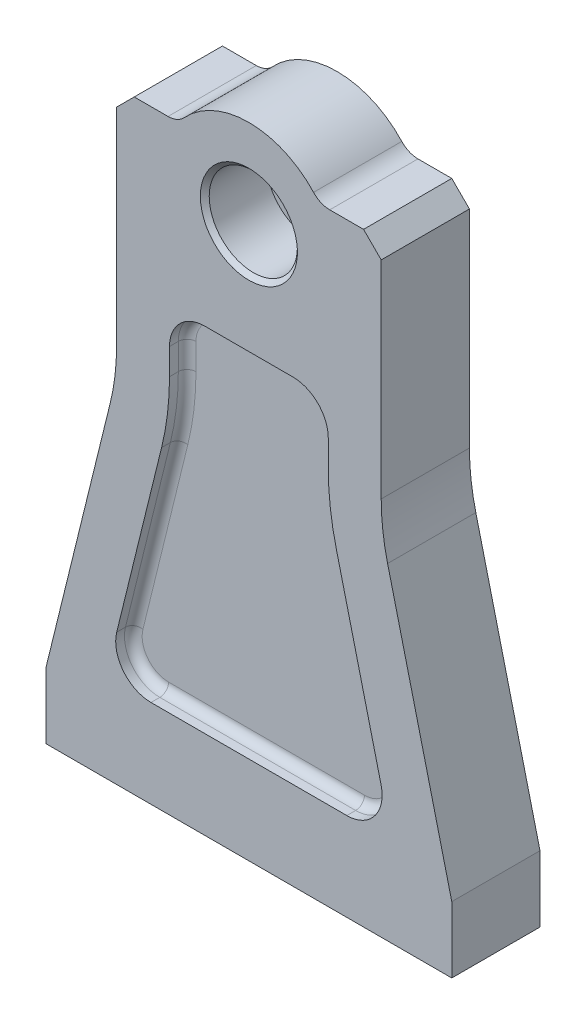
SolidWorks part; units mm, degrees
ref_plane "Front Plane" through (0, 0, 0) normal (0, 0, 1) x (1, 0, 0)
ref_plane "Top Plane" through (0, 0, 0) normal (0, 1, 0) x (1, 0, 0)
ref_plane "Right Plane" through (0, 0, 0) normal (1, 0, 0) x (0, 0, -1)
sketch "Sketch1" plane through (0, 0, 0) normal (0, 0, 1) x (1, 0, 0)
  line L0 (-46, 0) -> (46, 0)
  line L1 (46, 0) -> (46, 15)
  line L2 (46, 15) -> (31.4493, 74.1124)
  line L3 (30, 86.0633) -> (30, 137)
  line L4 (16, 137) -> (30, 137)
  line L5 (0, 0) -> (0, 200.804) construction
  line L6 (-16, 137) -> (-30, 137)
  line L7 (-30, 86.0633) -> (-30, 137)
  line L8 (-46, 15) -> (-31.4493, 74.1124)
  line L9 (-46, 0) -> (-46, 15)
  arc A0 (16, 137) -> (-16, 137) centre (0, 125) ccw
  circle A1 centre (0, 125) radius 6.5
  arc A2 (31.4493, 74.1124) -> (30, 86.0633) centre (80, 86.0633) cw
  arc A3 (-31.4493, 74.1124) -> (-30, 86.0633) centre (-80, 86.0633) ccw
  point P17 (30, 80)
  point P20 (-30, 80)
  dimension "D1" = 13
  dimension "D2" = 40
  dimension "D9" = 50
  dimension "D3" = 125
  dimension "D4" = 46
  dimension "D5" = 15
  dimension "D6" = 65
  dimension "D7" = 12
  dimension "D8" = 30
extrude "Boss-Extrude1" add sketch "Sketch1" along normal mid plane 20
sketch "Sketch2" plane through (0, 0, 10) normal (0, 0, 1) x (1, 0, 0)
  circle A0 centre (0, 125) radius 10
  dimension "D1" = 20
extrude "Cut-Extrude1" cut sketch "Sketch2" against normal blind 14
chamfer "Chamfer1" distance 1 angle 45 1 edges at (10, 125, 10)
chamfer "Chamfer2" distance 4 angle 45 2 edges at (30, 137, 0) (-30, 137, 0)
fillet "Fillet1" radius 5 2 edges at (16, 137, 0) (-16, 137, 0)
sketch3d "3DSketch3"
  line L0 (-18, 137.0109, 10) -> (-18, 86.0633, 10)
  line L1 (-19.7971, 71.2442, 10) -> (-37.3341, 0, 10)
  line L2 (-18, 137.0109, 10) -> (-18, 86.0633, 10)
  line L3 (-19.7971, 71.2442, 10) -> (-37.3341, 0, 10)
  line L4 (37.3341, 0, 10) -> (19.7971, 71.2442, 10)
  line L5 (18, 86.0633, 10) -> (18, 137.0109, 10)
  line L6 (37.3341, 0, 10) -> (19.7971, 71.2442, 10)
  line L7 (18, 86.0633, 10) -> (18, 137.0109, 10)
  spline S0 degree 5 poles (979.9272, 150.3528, 10) (366.7072, 141.5048, 10) (67.5037, 129.3382, 10) (-24.8839, 114.9859, 10) (-17.3153, 98.854, 10) (-18.0647, 82.8101, 10) (-18.1123, 82.0877, 10) (-18.2404, 80.5075, 10) (-18.4062, 78.9316, 10) (-18.5092, 78.0771, 10) (-18.7138, 76.5948, 10) (-18.9684, 75.1206, 10) (-19.0848, 74.4955, 10) (-19.2618, 73.6027, 10) (-19.4521, 72.7126, 10) (-19.511, 72.4447, 10) (-22.0166, 61.4386, 10) (-28.4768, 51.3904, 10) (62.2357, 18.0877, 10) (350.7446, -63.1243, 10) (937.8308, -216.6557, 10) knots -5.002278 -5.002278 -5.002278 -5.002278 -5.002278 -5.002278 0.120836 0.120836 0.120836 0.362509 0.362509 0.362509 0.650011 0.650011 0.650011 0.862509 0.862509 0.862509 0.95417 0.95417 0.95417 4.634695 4.634695 4.634695 4.634695 4.634695 4.634695 only from (-18, 86.0633, 10) to (-19.7971, 71.2442, 10)
  spline S1 degree 5 poles (-18, 86.0633, 10) (-18, 85.7018, 10) (-18, 85.3402, 10) (-18.0014, 84.9787, 10) (-18.0141, 83.8942, 10) (-18.0647, 82.8101, 10) (-18.1123, 82.0877, 10) (-18.2404, 80.5075, 10) (-18.4062, 78.9316, 10) (-18.5092, 78.0771, 10) (-18.7138, 76.5948, 10) (-18.9684, 75.1206, 10) (-19.0848, 74.4955, 10) (-19.2618, 73.6027, 10) (-19.4521, 72.7126, 10) (-19.511, 72.4447, 10) (-19.6024, 72.0436, 10) (-19.6989, 71.6437, 10) (-19.7315, 71.5105, 10) (-19.7643, 71.3773, 10) (-19.7971, 71.2442, 10) knots 0 0 0 0 0 0 0.120836 0.120836 0.120836 0.362509 0.362509 0.362509 0.650011 0.650011 0.650011 0.862509 0.862509 0.862509 0.95417 0.95417 0.95417 1 1 1 1 1 1
  spline S2 degree 5 poles (-933.8387, -229.7054, 10) (-340.5078, -74.5427, 10) (-52.8848, 8.7866, 10) (33.3944, 44.8054, 10) (22.1894, 58.6606, 10) (19.0823, 74.4186, 10) (18.9559, 75.1314, 10) (18.7026, 76.6964, 10) (18.4869, 78.2663, 10) (18.3826, 79.1207, 10) (18.2271, 80.6089, 10) (18.1219, 82.1012, 10) (18.0855, 82.736, 10) (18.044, 83.6452, 10) (18.016, 84.555, 10) (18.0092, 84.8292, 10) (17.8115, 96.1152, 10) (21.6827, 107.4162, 10) (-74.3605, 118.0717, 10) (-373.9181, 127.9706, 10) (-980.6842, 136.7277, 10) knots -5.002278 -5.002278 -5.002278 -5.002278 -5.002278 -5.002278 0.120836 0.120836 0.120836 0.362509 0.362509 0.362509 0.650011 0.650011 0.650011 0.862509 0.862509 0.862509 0.95417 0.95417 0.95417 4.634695 4.634695 4.634695 4.634695 4.634695 4.634695 only from (19.7971, 71.2442, 10) to (18, 86.0633, 10)
  spline S3 degree 5 poles (19.7971, 71.2442, 10) (19.7107, 71.5952, 10) (19.6242, 71.9463, 10) (19.5392, 72.2977, 10) (19.2923, 73.3538, 10) (19.0823, 74.4186, 10) (18.9559, 75.1314, 10) (18.7026, 76.6964, 10) (18.4869, 78.2663, 10) (18.3826, 79.1207, 10) (18.2271, 80.6089, 10) (18.1219, 82.1012, 10) (18.0855, 82.736, 10) (18.044, 83.6452, 10) (18.016, 84.555, 10) (18.0092, 84.8292, 10) (18.002, 85.2406, 10) (18.0002, 85.652, 10) (18, 85.7891, 10) (18, 85.9262, 10) (18, 86.0633, 10) knots 0 0 0 0 0 0 0.120836 0.120836 0.120836 0.362509 0.362509 0.362509 0.650011 0.650011 0.650011 0.862509 0.862509 0.862509 0.95417 0.95417 0.95417 1 1 1 1 1 1
  dimension "D1" = 12
  dimension "D2" = 12
sketch "Sketch10" plane through (0, 0, 10) normal (0, 0, 1) x (1, 0, 0)
  line L0 (-10, 100) -> (10, 100)
  line L13 (-46, 20) -> (46, 20)
  line L14 (-22.203, 20) -> (22.203, 20)
  line L22 (18, 86.0633) -> (18, 125.0032)
  line L23 (-18, 125.0032) -> (-18, 86.0633)
  line L24 (-19.7971, 71.2442) -> (-34, 13.5448)
  line L25 (-34, 13.5448) -> (-34, 12)
  line L26 (-34, 12) -> (34, 12)
  line L27 (34, 12) -> (34, 13.5448)
  line L28 (34, 13.5448) -> (19.7971, 71.2442)
  line L29 (18, 86.0633) -> (18, 92)
  line L30 (-18, 92) -> (-18, 86.0633)
  line L31 (-19.7971, 71.2442) -> (-29.9711, 29.9122)
  line L32 (-34, 13.5448) -> (-34, 12)
  line L34 (34, 12) -> (34, 13.5448)
  line L35 (29.9711, 29.9122) -> (19.7971, 71.2442)
  arc A0 (-22.203, 20) -> (-29.9711, 29.9122) centre (-22.203, 28) cw
  arc A1 (22.203, 20) -> (29.9711, 29.9122) centre (22.203, 28) ccw
  arc A2 (18, 92) -> (10, 100) centre (10, 92) ccw
  arc A3 (-18, 92) -> (-10, 100) centre (-10, 92) cw
  arc A10 (5.8657, 130.44) -> (18, 125.0032) centre (18.3303, 142) ccw
  arc A11 (5.8657, 130.44) -> (-5.8657, 130.44) centre (0, 125) ccw
  arc A12 (-18, 125.0032) -> (-5.8657, 130.44) centre (-18.3303, 142) ccw
  arc A13 (-19.7971, 71.2442) -> (-18, 86.0633) centre (-80, 86.0633) ccw
  arc A14 (18, 86.0633) -> (19.7971, 71.2442) centre (80, 86.0633) ccw
  arc A18 (-19.7971, 71.2442) -> (-18, 86.0633) centre (-80, 86.0633) ccw
  arc A19 (18, 86.0633) -> (19.7971, 71.2442) centre (80, 86.0633) ccw
  dimension "D4" = 8
  dimension "D3" = 80
  dimension "D1" = 12
  dimension "D2" = 20
extrude "Cut-Extrude2" cut sketch "Sketch10" against normal blind 4 contours A19 L29 A2 L0 A3 L30 A18 L31 A0 L14 A1 L35
fillet "Fillet2" radius 2 12 edges at (24.8841, 50.5782, 6) (28.4997, 23.0653, 6) (0, 20, 6) (-28.4997, 23.0653, 6) (-24.8841, 50.5782, 6) (-18.4509, 78.5995, 6) (-18, 89.0317, 6) (-15.6569, 97.6569, 6) (0, 100, 6) (15.6569, 97.6569, 6) (18, 89.0317, 6) (18.4509, 78.5995, 6)
mirror "Mirror2" about plane through (0, 0, 0) normal (0, 0, 1) of "Fillet2", "Cut-Extrude2"
hole_wizard "M10x1.25 Tapped Hole1" positions "Sketch11" profile "Sketch12" tap size "M10x1.25" standard "ISO"
sketch "Sketch11" plane through (0, 0, 0) normal (0, -1, 0) x (-1, 0, 0)
  line L1 (-46, -10) -> (-46, 10) construction
  point P0 (-30, 0)
  point P2 (30, 0)
  dimension "D3" = 16
  dimension "D4" = 60
cosmetic thread "Hole Thread1" parameters "D1"=20, "D2"=10
cosmetic thread "Hole Thread2" parameters "D1"=20, "D2"=10
sketch "Sketch12" plane through (30, 0, 0) normal (1, 0, 0) x (0, 0, -1)
  line L0 (0, 0) -> (0, 22.6438)
  line L1 (0, 22.6438) -> (4.4, 20)
  line L2 (4.4, 20) -> (4.4, 0.625)
  line L3 (4.4, 0.625) -> (5.025, 0)
  line L5 (5.025, 0) -> (0, 0)
  line L6 (-4.4, 0.625) -> (-5.025, 0) construction
  line L10 (0, 22.6438) -> (-4.4, 20) construction
  line L11 (0, -6.35) -> (0, 107.95) construction
  dimension "Tap Drill Dia." = 8.8
  dimension "Tap Drill Depth" = 20
  dimension "Near C'Sink Dia." = 10.05
  dimension "Near C'Sink Angle" = 90
  dimension "Drill Angle" = 118
